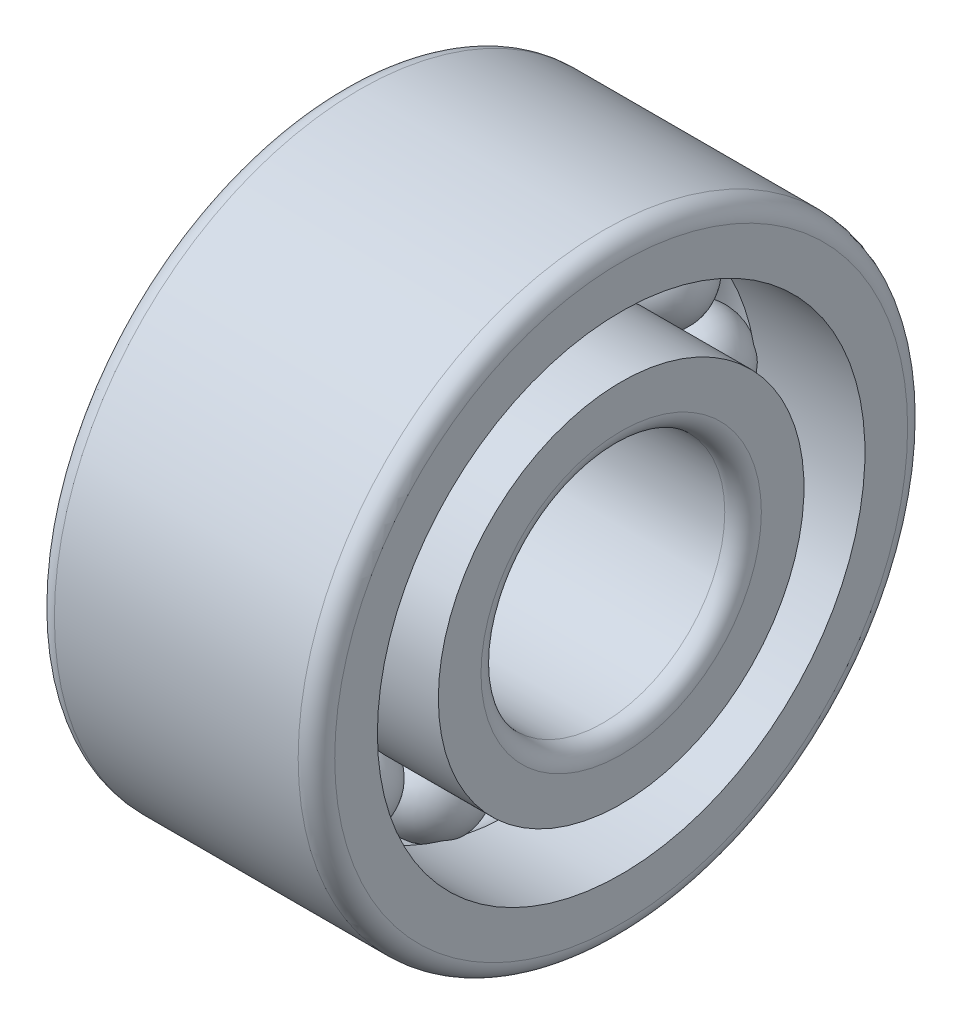
SolidWorks part; units mm, degrees
ref_plane "Front" through (0, 0, 0) normal (0, 0, 1) x (1, 0, 0)
ref_plane "Top" through (0, 0, 0) normal (0, 1, 0) x (1, 0, 0)
ref_plane "Right" through (0, 0, 0) normal (1, 0, 0) x (0, 0, -1)
sketch "Sketch1" plane through (0, 0, 0) normal (0, 0, 1) x (1, 0, 0)
  line L0 (-9.6833, 0) -> (9.8371, 0) construction
  line L1 (-0.375, 1.75) -> (0.375, 1.75)
  line L2 (-4.5966, 1.75) -> (4.6657, 1.75) construction
  arc A0 (0.375, 1.75) -> (-0.375, 1.75) centre (0, 1.75) ccw
  dimension "dia" = 0.75
  dimension "d0" = 3.5
revolve "Revolve1" add sketch "Sketch1" angle 360 about L2
sketch "Sketch2" plane through (0, 0, 0) normal (0, 0, 1) x (1, 0, 0)
  line L0 (-1.15, 1.5) -> (-1.15, 1)
  line L1 (-1.15, 1) -> (1.15, 1)
  line L2 (1.15, 1) -> (1.15, 1.5)
  line L3 (1.15, 1.5) -> (0.2659, 1.5)
  line L4 (-6.9714, 0) -> (8.1665, 0) construction
  line L5 (-6.7058, 1.75) -> (6.7058, 1.75) construction
  line L6 (-0.2659, 1.5) -> (-1.15, 1.5)
  arc A0 (-0.2659, 1.5) -> (0.2659, 1.5) centre (0, 1.75) ccw
  dimension "B" = 2.3
  dimension "B/2" = 1.15
  dimension "D5" = 0.73
  dimension "d" = 2
  dimension "D3" = 1.75
  dimension "D4" = 0.5
revolve "Revolve2" add sketch "Sketch2" angle 360 about L4
sketch "Sketch3" plane through (0, 0, 0) normal (0, 0, 1) x (1, 0, 0)
  line L0 (-8.7107, 0) -> (9.1288, 0) construction
  line L1 (-1.15, 2.5) -> (1.15, 2.5)
  line L2 (-1.15, 2.5) -> (-1.15, 2)
  line L3 (-1.15, 2) -> (-0.2659, 2)
  line L4 (1.15, 2.5) -> (1.15, 2)
  line L5 (-7.2948, 1.75) -> (7.2948, 1.75) construction
  line L6 (0.2659, 2) -> (1.15, 2)
  arc A0 (0.2659, 2) -> (-0.2659, 2) centre (0, 1.75) ccw
  dimension "D1" = 0.73
  dimension "DD" = 5
  dimension "B" = 2.3
  dimension "D4" = 1.75
  dimension "D5" = 0.5
  dimension "B/2" = 1.15
revolve "Revolve3" add sketch "Sketch3" angle 360 about L0
pattern_circular "Circular-Pattern1" count 13 over 360 about axis through (0, 0, 0) along (1, 0, 0) of "Revolve1"
fillet "Fillet1" radius 0.15 4 edges at (-1.15, 0, 1) (-1.15, 0, 2.5) (1.15, 0, 2.5) (1.15, 0, 1)
equation "\"d0@Sketch1\" = ( \"DD@Sketch3\" + \"d@Sketch2\" )  / 2"
equation "\"dia@Sketch1\" =  ( \"DD@Sketch3\" - \"d@Sketch2\" )  / 4"
equation "\"D3@Sketch2\" = ( \"DD@Sketch3\" + \"d@Sketch2\" )  / 2 / 2"
equation "\"D4@Sketch2\" = ( \"DD@Sketch3\" - \"d@Sketch2\" )  / 6"
equation "\"D5@Sketch2\" = \"dia@Sketch1\" - 0.02"
equation "\"B/2@Sketch2\" = \"B@Sketch2\" / 2"
equation "\"D4@Sketch3\" = ( \"DD@Sketch3\" + \"d@Sketch2\" )  / 2 / 2"
equation "\"D5@Sketch3\" = ( \"DD@Sketch3\" - \"d@Sketch2\" )  / 6"
equation "\"B@Sketch3\" = \"B@Sketch2\""
equation "\"B/2@Sketch3\" = \"B@Sketch3\" / 2"
equation "\"D1@Sketch3\" = \"dia@Sketch1\" - 0.02"
equation "\"m@Circular-Pattern1\" = int( 3.14159265 / atn(( \"dia@Sketch1\" / 2) / sqr(( \"DD@Sketch3\" + \"d@Sketch2\" )  / 2 * ( \"DD@Sketch3\" + \"d@Sketch2\" )  / 2/4 - ( \"dia@Sketch1\" / 2) *  ( \"dia@Sketch1\" / 2))))-1"
